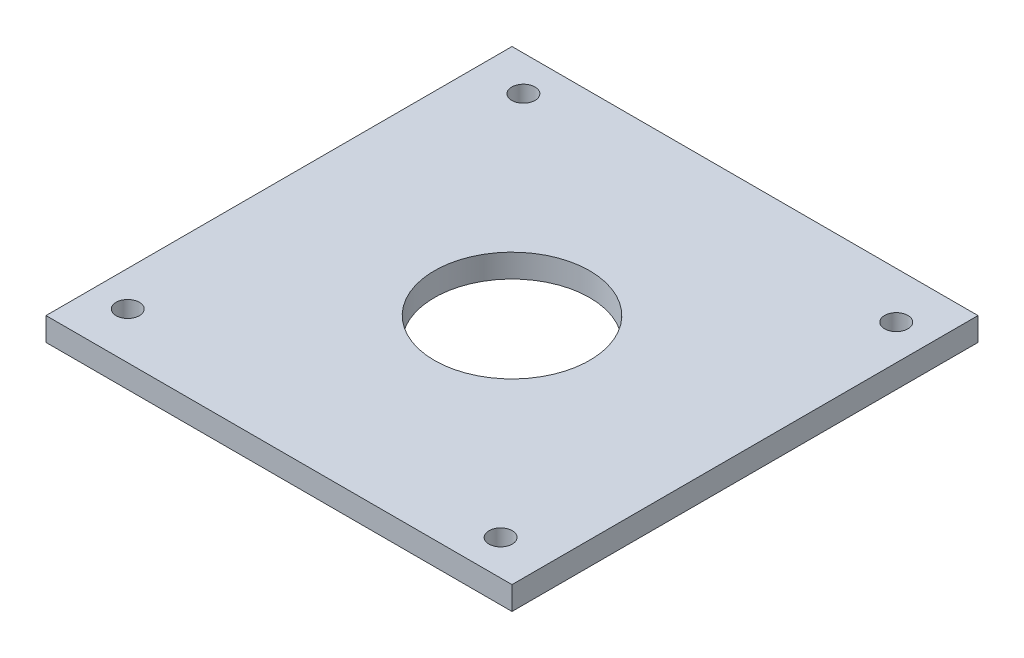
SolidWorks part; units mm, degrees
ref_plane "前视基准面" through (0, 0, 0) normal (0, 0, 1) x (1, 0, 0)
ref_plane "上视基准面" through (0, 0, 0) normal (0, 1, 0) x (1, 0, 0)
ref_plane "右视基准面" through (0, 0, 0) normal (1, 0, 0) x (0, 0, -1)
sketch "草图1" plane through (0, 0, 0) normal (0, 1, 0) x (1, 0, 0)
  line L1 (-25.4709, 24.0049) -> (25.4709, 24.0049) construction
  line L2 (-25.4709, 24.0049) -> (-25.4709, -24.0049) construction
  line L3 (-25.4709, -24.0049) -> (25.4709, -24.0049) construction
  line L4 (25.4709, 24.0049) -> (25.4709, -24.0049) construction
  line L5 (-25.4709, 24.0049) -> (25.4709, -24.0049) construction
  line L6 (-25.4709, -24.0049) -> (25.4709, 24.0049) construction
  line L7 (-30, 30) -> (30, 30)
  line L8 (-30, 30) -> (-30, -30)
  line L9 (-30, -30) -> (30, -30)
  line L10 (30, 30) -> (30, -30)
  line L11 (-30, 30) -> (30, -30) construction
  line L12 (-30, -30) -> (30, 30) construction
  circle A0 centre (0, 0) radius 35 construction
  circle A1 centre (25.4709, 24.0049) radius 1.5
  circle A5 centre (0, 0) radius 10
  circle A6 centre (24.0049, -25.4709) radius 1.5
  circle A7 centre (-25.4709, -24.0049) radius 1.5
  circle A8 centre (-24.0049, 25.4709) radius 1.5
  point P0 (0, 0)
  point P23 (0, 0)
  dimension "D1" = 70
  dimension "D2" = 3
  dimension "D6" = 20
  dimension "D3" = 48.0098
  dimension "D4" = 60
  dimension "D5" = 60
  dimension "D7" = 4
extrude "凸台-拉伸1" add sketch "草图1" along normal blind 3
